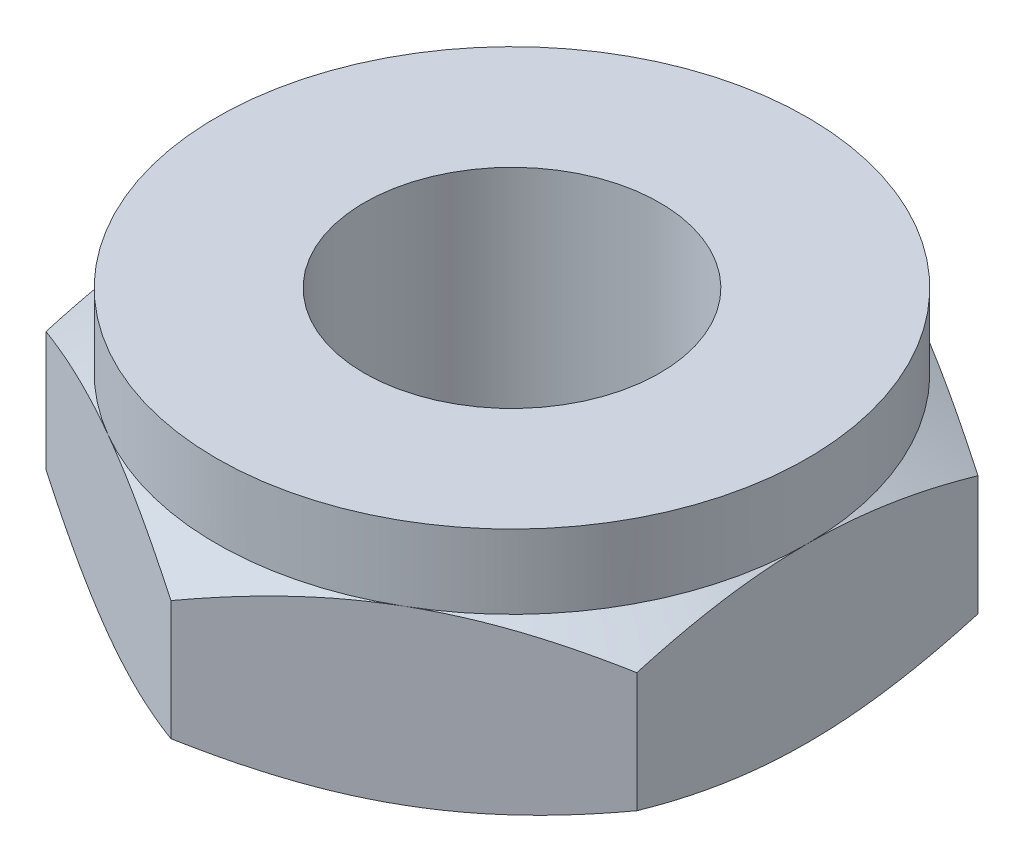
SolidWorks part; units mm, degrees
material "Chrome Stainless Steel"
ref_plane "Front Plane" through (0, 0, 0) normal (0, 0, 1) x (1, 0, 0)
ref_plane "Top Plane" through (0, 0, 0) normal (0, 1, 0) x (1, 0, 0)
ref_plane "Right Plane" through (0, 0, 0) normal (1, 0, 0) x (0, 0, -1)
sketch "BodyS" plane through (0, 0, 0) normal (0, 1, 0) x (1, 0, 0)
  line L1 (-6, 3.4641) -> (-6, -3.4641)
  line L2 (-6, -3.4641) -> (0, -6.9282)
  line L3 (0, -6.9282) -> (6, -3.4641)
  line L4 (6, -3.4641) -> (6, 3.4641)
  line L5 (6, 3.4641) -> (0, 6.9282)
  line L6 (0, 6.9282) -> (-6, 3.4641)
  circle A0 centre (0, 0) radius 6 construction
  circle A1 centre (0, 0) radius 3
  dimension "Thread Size" = 6
  dimension "Hex" = 12
extrude "Body" add sketch "BodyS" along normal mid plane 3.5
sketch "ChamferS" plane through (0, 1.75, 0) normal (0, 1, 0) x (1, 0, 0)
  circle A0 centre (0, 0) radius 6 construction
  circle A1 centre (0, 0) radius 6
extrude "Chamfer" cut sketch "ChamferS" against normal through all draft 60 flip side to cut
mirror "CM" about plane through (0, 0, 0) normal (0, 1, 0) of "Chamfer"
sketch "FasteningBaseS" plane through (0, 1.75, 0) normal (0, 1, 0) x (1, 0, 0)
  circle A6 centre (0, 0) radius 3 construction
  circle A7 centre (0, 0) radius 3
  circle A8 centre (0, 0) radius 6
  arc A9 (-3, -5.1962) -> (3, -5.1962) centre (0, 0) ccw construction
extrude "FasteningBase" add sketch "FasteningBaseS" along normal blind 1.5
